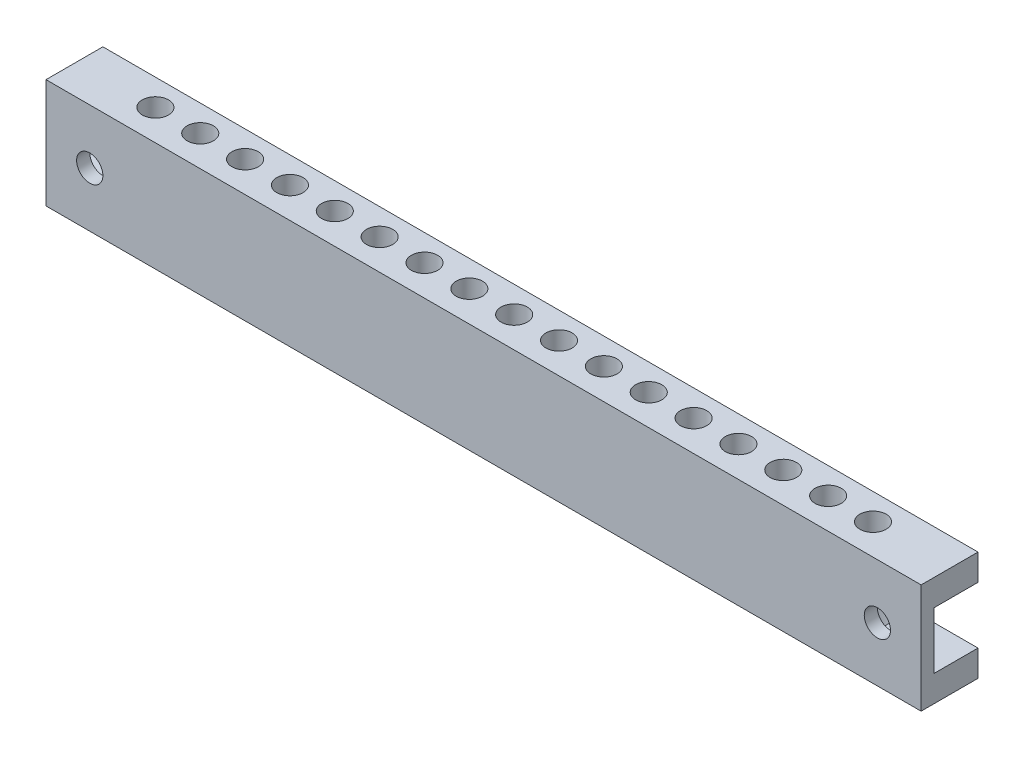
SolidWorks part; units mm, degrees
ref_plane "Front Plane" through (0, 0, 0) normal (0, 0, 1) x (1, 0, 0)
ref_plane "Top Plane" through (0, 0, 0) normal (0, 1, 0) x (1, 0, 0)
ref_plane "Right Plane" through (0, 0, 0) normal (1, 0, 0) x (0, 0, -1)
sketch "Sketch1" plane through (0, 0, 0) normal (0, 0, 1) x (1, 0, 0)
  line L0 (0, 0) -> (0, 41.6923) construction
  line L2 (-50, -6.25) -> (50, -6.25)
  line L3 (-50, -6.25) -> (-50, 6.25)
  line L4 (-50, 6.25) -> (50, 6.25)
  line L5 (50, -6.25) -> (50, 6.25)
  line L6 (-50, -6.25) -> (50, 6.25) construction
  line L7 (-50, 6.25) -> (50, -6.25) construction
  dimension "D1" = 12.5
  dimension "D2" = 100
extrude "Boss-Extrude1" add sketch "Sketch1" along normal blind 1.5
sketch "Sketch2" plane through (0, 0, 0) normal (0, 0, -1) x (-1, 0, 0)
  line L0 (-23.7197, 0) -> (25.26, 0) construction
  line L1 (50, 6.25) -> (50, -6.25) construction
  line L2 (-50, 6.25) -> (50, 6.25)
  line L3 (-50, 6.25) -> (-50, 3.25)
  line L4 (-50, 3.25) -> (50, 3.25)
  line L5 (50, 6.25) -> (50, 3.25)
  line L6 (-50, -3.25) -> (50, -3.25)
  line L7 (50, -6.25) -> (50, -3.25)
  line L8 (-50, -6.25) -> (50, -6.25)
  line L9 (-50, -6.25) -> (-50, -3.25)
  dimension "D1" = 3
extrude "Boss-Extrude2" add sketch "Sketch2" along normal blind 5
sketch "Sketch3" plane through (0, -6.25, 0) normal (0, -1, 0) x (1, 0, 0)
  line L0 (0, 0) -> (0, -19.0736) construction
  line L1 (-50, -1.75) -> (54.5359, -1.75) construction
  line L2 (-50, 1.5) -> (-50, -5) construction
  line L3 (50, -2) -> (-59.9935, -2) construction
  line L4 (50, 1.5) -> (50, -5) construction
  line L8 (-50, 1.5) -> (50, 1.5) construction
  circle A0 centre (41, -2) radius 1.5
  circle A1 centre (35.875, -2) radius 1.5
  circle A2 centre (30.75, -2) radius 1.5
  circle A3 centre (25.625, -2) radius 1.5
  circle A4 centre (20.5, -2) radius 1.5
  circle A5 centre (15.375, -2) radius 1.5
  circle A6 centre (10.25, -2) radius 1.5
  circle A7 centre (5.125, -2) radius 1.5
  circle A8 centre (0, -2) radius 1.5
  circle A9 centre (-5.125, -2) radius 1.5
  circle A10 centre (-10.25, -2) radius 1.5
  circle A11 centre (-15.375, -2) radius 1.5
  circle A12 centre (-20.5, -2) radius 1.5
  circle A13 centre (-25.625, -2) radius 1.5
  circle A14 centre (-30.75, -2) radius 1.5
  circle A15 centre (-35.875, -2) radius 1.5
  circle A16 centre (-41, -2) radius 1.5
  dimension "D2" = 17
  dimension "D3" = 3
  dimension "D4" = 9
  dimension "D5" = 9
  dimension "D1" = 3.5
extrude "Cut-Extrude1" cut sketch "Sketch3" against normal through all and the other way through all
sketch "Sketch4" plane through (0, 0, 0) normal (0, 0, -1) x (-1, 0, 0)
  line L0 (-50, 0) -> (53.5091, 0) construction
  line L1 (-50, -3.25) -> (-50, 3.25) construction
  line L2 (0, 0) -> (0, 16.2581) construction
  circle A0 centre (-45, 0) radius 1.5
  circle A1 centre (45, 0) radius 1.5
  dimension "D1" = 3
  dimension "D2" = 5
extrude "Cut-Extrude2" cut sketch "Sketch4" against normal through all
